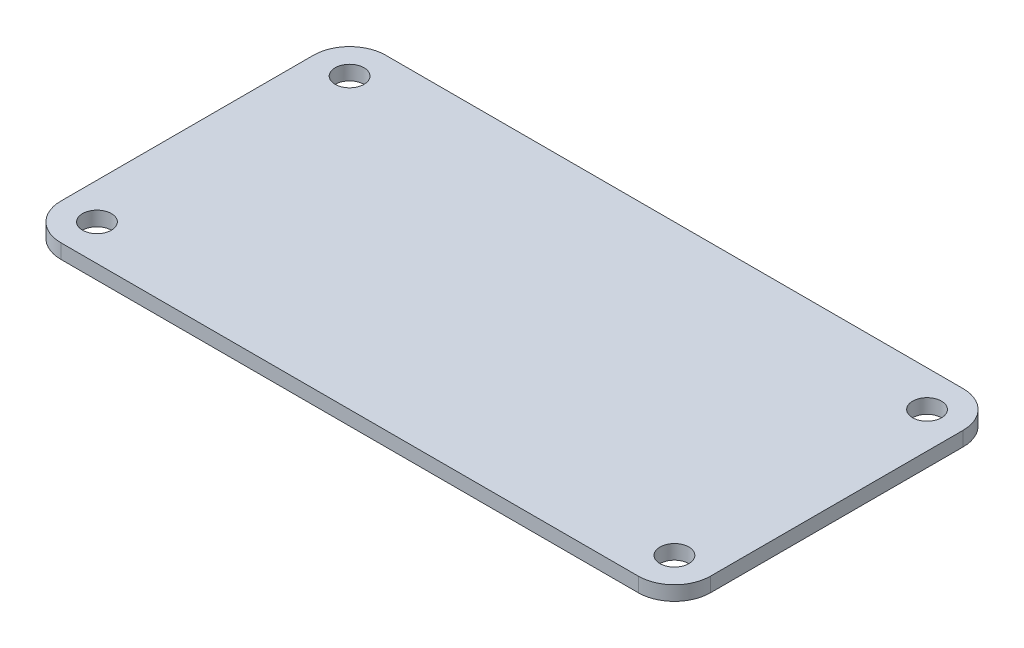
SolidWorks part; units mm, degrees
ref_plane "Alzado" through (0, 0, 0) normal (0, 0, 1) x (1, 0, 0)
ref_plane "Planta" through (0, 0, 0) normal (0, 1, 0) x (1, 0, 0)
ref_plane "Vista lateral" through (0, 0, 0) normal (1, 0, 0) x (0, 0, -1)
sketch "Croquis2" plane through (0, 0, 0) normal (0, 1, 0) x (1, 0, 0)
  line L1 (-90, -45) -> (90, -45)
  line L2 (-90, -45) -> (-90, 45)
  line L3 (-90, 45) -> (90, 45)
  line L4 (90, -45) -> (90, 45)
  line L5 (-90, -45) -> (90, 45) construction
  line L6 (-90, 45) -> (90, -45) construction
  point P0 (0, 0)
  dimension "D1" = 90
  dimension "D2" = 180
extrude "Saliente-Extruir1" add sketch "Croquis2" along normal blind 4
fillet "Redondeo1" radius 10 4 edges at (90, 2, 45) (90, 2, -45) (-90, 2, -45) (-90, 2, 45)
sketch "Croquis4" plane through (0, 4, 0) normal (0, 1, 0) x (1, 0, 0)
  line L0 (0, 0) -> (0, 59.7635) construction
  circle A0 centre (-80, 35) radius 4
  circle A1 centre (-80, -35) radius 4
  circle A4 centre (80, -35) radius 4
  circle A5 centre (80, 35) radius 4
  dimension "D1" = 8
extrude "Cortar-Extruir2" cut sketch "Croquis4" against normal up to next
